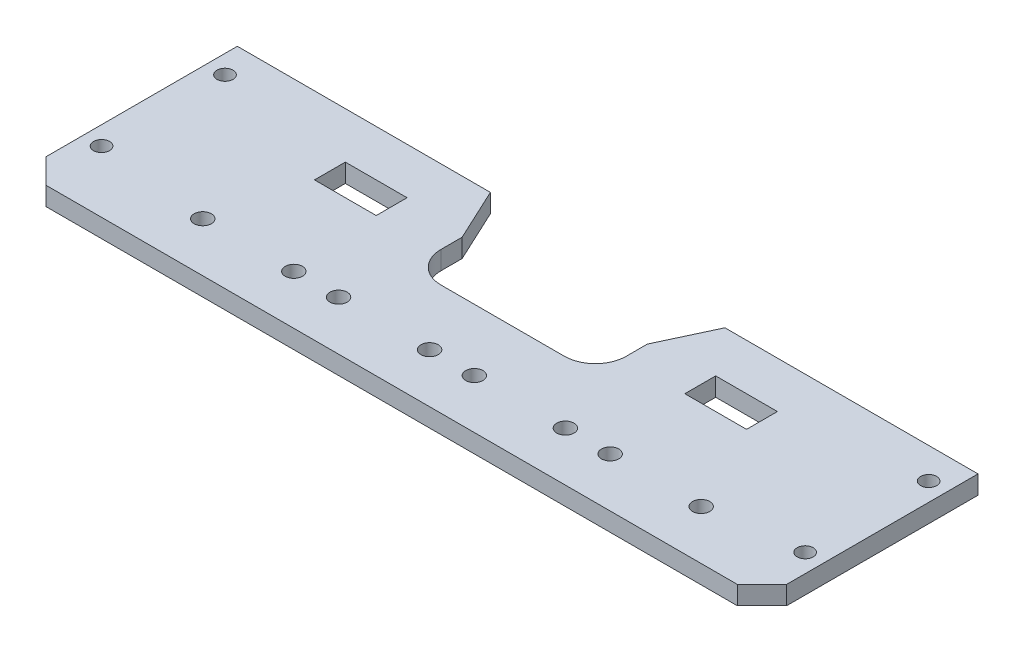
SolidWorks part; units mm, degrees
ref_plane "前视基准面" through (0, 0, 0) normal (0, 0, 1) x (1, 0, 0)
ref_plane "上视基准面" through (0, 0, 0) normal (0, 1, 0) x (1, 0, 0)
ref_plane "右视基准面" through (0, 0, 0) normal (1, 0, 0) x (0, 0, -1)
sketch "草图1" plane through (0, 0, 0) normal (0, 1, 0) x (1, 0, 0)
  line L1 (-60, 17.5) -> (60, 17.5)
  line L2 (-60, 17.5) -> (-60, -17.5)
  line L3 (-60, -17.5) -> (60, -17.5)
  line L4 (60, 17.5) -> (60, -17.5)
  line L5 (-60, 17.5) -> (60, -17.5) construction
  line L6 (-60, -17.5) -> (60, 17.5) construction
  point P0 (0, 0)
  dimension "D1" = 120
  dimension "D2" = 35
extrude "凸台-拉伸1" add sketch "草图1" along normal blind 3
sketch "草图2" plane through (0, 3, 0) normal (0, 1, 0) x (1, 0, 0)
  line L0 (0, 17.5) -> (0, -17.5) construction
  line L1 (60, 17.5) -> (-60, 17.5) construction
  line L2 (-60, -17.5) -> (60, -17.5) construction
  line L3 (15, 17.5) -> (-15, 17.5)
  line L4 (-15, 17.5) -> (-15, 0.5)
  line L5 (-15, 0.5) -> (15, 0.5)
  line L6 (15, 17.5) -> (15, 0.5)
  point P10 (0, 0.5)
  dimension "D1" = 18
  dimension "D2" = 30
extrude "切除-拉伸1" cut sketch "草图2" against normal through all
sketch "草图3" plane through (0, 3, 0) normal (0, 1, 0) x (1, 0, 0)
  line L0 (0, -17.5) -> (0, 15) construction
  line L1 (-60, -17.5) -> (60, -17.5) construction
  line L2 (-57, 12.5) -> (-57, -7.5) construction
  line L3 (-60, 17.5) -> (-60, -17.5) construction
  line L4 (-15, 17.5) -> (-60, 17.5) construction
  circle A0 centre (-57, 12.5) radius 1.3
  circle A1 centre (-57, -7.5) radius 1.3
  circle A2 centre (57, -7.5) radius 1.3
  circle A3 centre (57, 12.5) radius 1.3
  dimension "D1" = 3
  dimension "D2" = 5
  dimension "D3" = 20
extrude "切除-拉伸2" cut sketch "草图3" against normal through all
sketch "草图4" plane through (0, 3, 0) normal (0, 1, 0) x (1, 0, 0)
  line L0 (0, -17.5) -> (0, 15) construction
  line L1 (-60, -17.5) -> (60, -17.5) construction
  line L2 (-44.7708, -9.5) -> (43.4775, -9.5) construction
  circle A0 centre (5.4, -9.5) radius 1.4
  circle A1 centre (20.15, -9.5) radius 1.4
  circle A2 centre (27.4, -9.5) radius 1.4
  circle A3 centre (42.15, -9.5) radius 1.4
  circle A4 centre (-1.85, -9.5) radius 1.4
  circle A5 centre (-16.6, -9.5) radius 1.4
  circle A6 centre (-23.85, -9.5) radius 1.4
  circle A7 centre (-38.6, -9.5) radius 1.4
  dimension "D2" = 8
  dimension "D3" = 14.75
  dimension "D4" = 14.75
  dimension "D5" = 14.75
  dimension "D6" = 14.75
  dimension "D7" = 2.8
  dimension "D8" = 2.8
  dimension "D9" = 2.8
  dimension "D10" = 2.8
  dimension "D11" = 7.25
  dimension "D13" = 7.25
  dimension "D14" = 7.25
  dimension "D15" = 2.8
  dimension "D12" = 4
extrude "切除-拉伸3" cut sketch "草图4" against normal through all
sketch "草图5" plane through (0, 3, 0) normal (0, 1, 0) x (1, 0, 0)
  line L0 (0, 15.4204) -> (0, -17.5) construction
  line L1 (-60, -17.5) -> (60, -17.5) construction
  line L2 (-15, 17.5) -> (-60, 17.5) construction
  line L3 (-35, 10) -> (-25, 10)
  line L4 (-35, 10) -> (-35, 5)
  line L5 (-35, 5) -> (-25, 5)
  line L6 (-25, 10) -> (-25, 5)
  line L7 (-35, 10) -> (-25, 5) construction
  line L8 (-35, 5) -> (-25, 10) construction
  line L10 (25, 10) -> (25, 5)
  line L11 (35, 5) -> (25, 5)
  line L12 (35, 10) -> (35, 5)
  line L13 (35, 10) -> (25, 10)
  point P4 (-30, 7.5)
  dimension "D1" = 10
  dimension "D2" = 5
  dimension "D3" = 10
  dimension "D4" = 30
extrude "切除-拉伸4" cut sketch "草图5" against normal through all
chamfer "倒角1" distance 4 angle 65 1 edges at (-15, 1.5, -17.5)
chamfer "倒角2" distance 4 angle 65 1 edges at (15, 1.5, -17.5)
fillet "圆角1" radius 5 2 edges at (15, 1.5, -0.5) (-15, 1.5, -0.5)
chamfer "倒角3" distance 4 angle 45 2 edges at (60, 1.5, 17.5) (-60, 1.5, 17.5)
